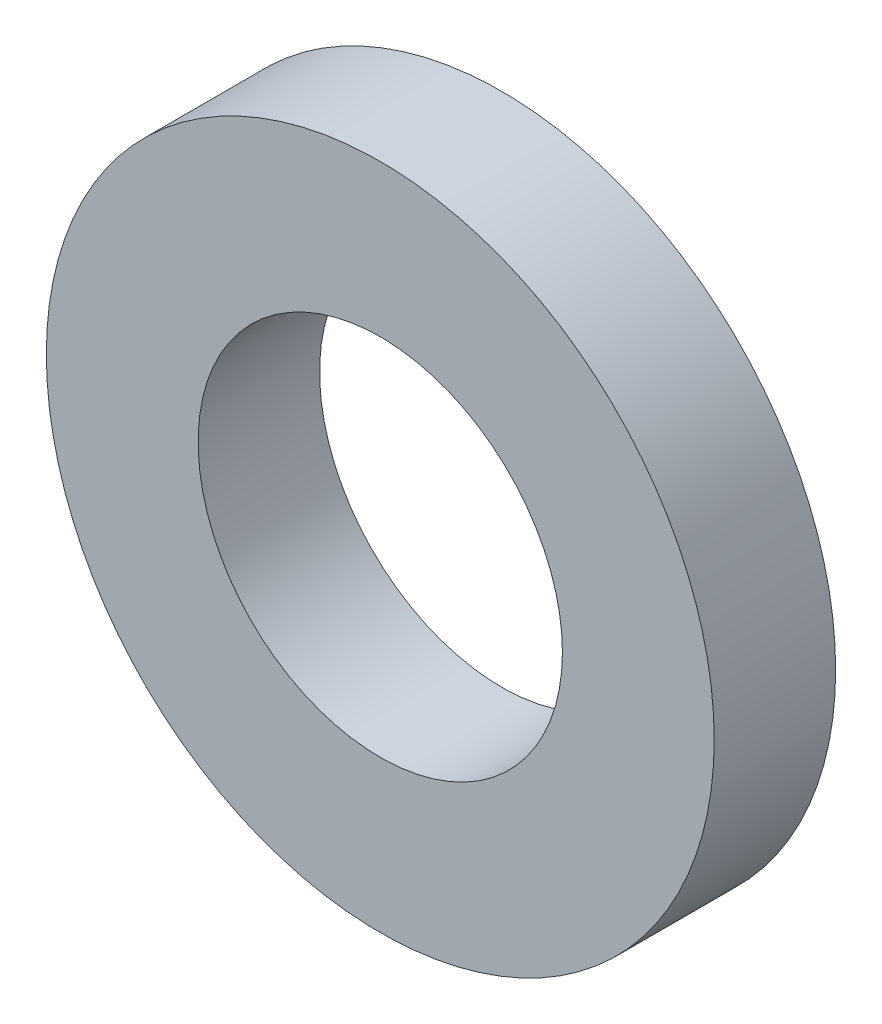
SolidWorks part; units mm, degrees
ref_plane "Front Plane" through (0, 0, 0) normal (0, 0, 1) x (1, 0, 0)
ref_plane "Top Plane" through (0, 0, 0) normal (0, 1, 0) x (1, 0, 0)
ref_plane "Right Plane" through (0, 0, 0) normal (1, 0, 0) x (0, 0, -1)
sketch "Sketch1" plane through (0, 0, 0) normal (0, 0, 1) x (1, 0, 0)
  circle A0 centre (0, 0) radius 15
  circle A1 centre (0, 0) radius 27.5
  dimension "D1" = 30
  dimension "D2" = 55
extrude "Boss-Extrude1" add sketch "Sketch1" along normal blind 10
